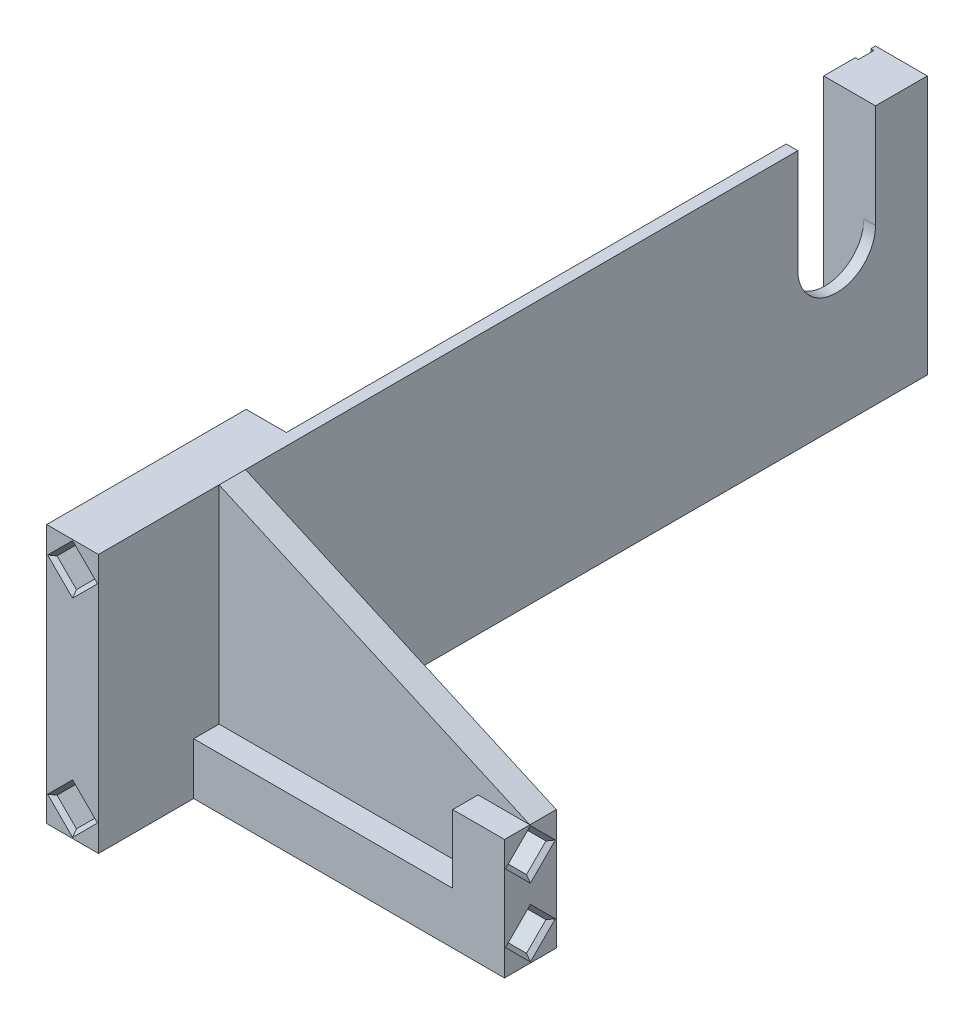
SolidWorks part; units mm, degrees
ref_plane "Front Plane" through (0, 0, 0) normal (0, 0, 1) x (1, 0, 0)
ref_plane "Top Plane" through (0, 0, 0) normal (0, 1, 0) x (1, 0, 0)
ref_plane "Right Plane" through (0, 0, 0) normal (1, 0, 0) x (0, 0, -1)
sketch "Sketch2" plane through (0, 0, 0) normal (0, 1, 0) x (1, 0, 0)
  line L0 (25.75, 56.5) -> (25.75, 62.5) construction
  line L1 (31.75, 62.5) -> (-31.75, 62.5) construction
  line L2 (31.75, 62.5) -> (31.75, -62.5) construction
  line L3 (31.75, -62.5) -> (-31.75, -62.5) construction
  line L4 (-31.75, 62.5) -> (-31.75, -62.5) construction
  line L5 (25.75, 56.5) -> (31.75, 56.5) construction
  line L6 (-25.75, -56.5) -> (-31.75, -56.5) construction
  line L7 (-25.75, -56.5) -> (-25.75, -62.5) construction
  point P4 (0, -56.5)
  point P5 (25.75, -56.5)
  point P6 (0, 56.5)
  point P8 (25.75, 56.5)
  point P12 (-25.75, -56.5)
  point P13 (0, -62.5)
  point P14 (-25.75, 56.5)
  point P17 (31.75, 0)
  dimension "D1" = 63.5
  dimension "D2" = 125
  dimension "D3" = 6
  dimension "D4" = 6
sketch "Sketch3" plane through (0, 0, 0) normal (0, 1, 0) x (1, 0, 0)
  line L0 (-31.75, 62.5) -> (-31.75, -62.5) construction
  line L1 (-29.21, 50.2117) -> (-37.6767, 50.2117)
  line L2 (-29.21, 50.2117) -> (-29.21, -61.23)
  line L3 (-29.21, -85.255) -> (-37.6767, -85.255)
  line L4 (-37.6767, 50.2117) -> (-37.6767, -85.255)
  line L6 (31.75, -62.5) -> (-31.75, -62.5) construction
  line L8 (-29.21, -61.23) -> (21.59, -61.23)
  line L10 (-29.21, -69.6967) -> (21.59, -69.6967)
  line L11 (21.59, -61.23) -> (21.59, -69.6967)
  line L13 (-29.21, -69.6967) -> (-29.21, -85.255)
  point P4 (-33.4433, 50.2117)
  dimension "D1" = 135.4667
  dimension "D2" = 8.4667
  dimension "D3" = 1.27
  dimension "D4" = 1.6933
  dimension "D5" = 50.8
  dimension "D6" = 15.5583
  dimension "D7" = 8.4667
extrude "Boss-Extrude2" add sketch "Sketch3" along normal blind 8.4667
sketch "Sketch12" plane through (0, 0, 0) normal (0, 1, 0) x (1, 0, 0)
  line L2 (-29.21, -61.23) -> (-29.21, 50.2117) construction
  line L5 (-25.75, -51.77) -> (-29.21, -51.77)
  line L6 (-25.75, -61.23) -> (-29.21, -61.23)
  line L7 (-29.21, -51.77) -> (-29.21, -61.23)
  line L8 (-25.75, -56.5) -> (-25.75, -62.5) construction
  line L9 (21.59, -61.23) -> (-29.21, -61.23) construction
  arc A1 (-25.75, -61.23) -> (-25.75, -51.77) centre (-25.75, -56.5) ccw
extrude "Boss-Extrude4" add sketch "Sketch12" along normal blind 3.175
sketch "Sketch14" plane through (0, 3.175, 0) normal (0, 1, 0) x (1, 0, 0)
  point P0 (-25.75, 56.5)
  point P1 (-25.75, -56.5)
hole_wizard "#24 (0.152) Diameter Hole1" positions "Sketch14" profile "Sketch15" hole size "#24" standard "ANSI Inch" end condition up to next
sketch "Sketch15" plane through (-25.75, 3.175, -56.5) normal (1, 0, 0) x (0, 0, 1)
  line L0 (0, 0) -> (0, 3.175)
  line L1 (0, 3.175) -> (1.9304, 3.175)
  line L2 (1.9304, 3.175) -> (1.9304, 0)
  line L5 (1.9304, 0) -> (0, 0)
  line L11 (0, -6.35) -> (0, 107.95) construction
  dimension "Thru Hole Dia." = 3.8608
  dimension "Thru Hole Depth" = 3.175
sketch "Sketch16" plane through (0, 8.4667, 0) normal (0, 1, 0) x (1, 0, 0)
  line L0 (-37.6767, -85.255) -> (-37.6767, -52.6472)
  line L1 (-29.21, -61.23) -> (-29.21, 50.2117) construction
  line L2 (-37.6767, 50.2117) -> (-29.21, 50.2117)
  line L5 (-37.6767, 41.745) -> (-31.115, 41.745)
  line L6 (-31.115, 41.745) -> (-31.115, -52.6472)
  line L7 (-31.115, -52.6472) -> (-37.6767, -52.6472)
  line L8 (-37.6767, 41.745) -> (-37.6767, 50.2117)
  line L9 (-29.21, -5.5092) -> (-31.115, -5.5092) construction
  line L11 (-37.6767, 50.2117) -> (-37.6767, -85.255) construction
  line L12 (-29.21, -85.255) -> (-37.6767, -85.255)
  line L13 (-29.21, -85.255) -> (-29.21, 50.2117)
  line L16 (-29.21, -61.23) -> (-29.21, 50.2117) construction
  dimension "D1" = 1.905
  dimension "D2" = 8.4667
extrude "Boss-Extrude5" add sketch "Sketch16" along normal blind 33.8667
sketch "Sketch19" plane through (0, 8.4667, 0) normal (0, 1, 0) x (1, 0, 0)
  line L0 (-29.21, -69.6967) -> (21.59, -69.6967) construction
  line L1 (21.59, -61.23) -> (13.1233, -61.23)
  line L2 (21.59, -61.23) -> (21.59, -69.6967)
  line L3 (21.59, -69.6967) -> (13.1233, -69.6967)
  line L4 (13.1233, -61.23) -> (13.1233, -69.6967)
extrude "Boss-Extrude7" add sketch "Sketch19" along normal blind 11.1417
sketch "Sketch18" plane through (0, 0, 61.23) normal (0, 0, -1) x (-1, 0, 0)
  line L0 (-21.59, 19.6083) -> (29.21, 42.3333)
  line L1 (-13.1233, 8.4667) -> (29.21, 8.4667) construction
  line L3 (29.21, 42.3333) -> (37.6767, 42.3333) construction
  line L4 (29.21, 42.3333) -> (29.21, 0) construction
  line L5 (29.21, 42.3333) -> (29.21, 8.4667)
  line L8 (-21.59, 19.6083) -> (-21.59, 0) construction
  line L9 (-21.59, 19.6083) -> (-13.1233, 19.6083)
  line L10 (-13.1233, 19.6083) -> (-13.1233, 8.4667)
  line L11 (-13.1233, 8.4667) -> (29.21, 8.4667)
extrude "Boss-Extrude6" add sketch "Sketch18" against normal blind 4.318
sketch "Sketch4" plane through (0, 0, 85.255) normal (0, 0, 1) x (1, 0, 0)
  line L0 (-36.6183, 4.2333) -> (-33.4433, 7.4083)
  line L1 (-36.6183, 4.2333) -> (-33.4433, 1.0583)
  line L2 (-33.4433, 7.4083) -> (-30.2683, 4.2333)
  line L3 (-33.4433, 1.0583) -> (-30.2683, 4.2333)
  line L4 (-36.6183, 4.2333) -> (-30.2683, 4.2333) construction
  line L5 (-33.4433, 7.4083) -> (-33.4433, 1.0583) construction
  line L6 (-37.6767, 8.4667) -> (-29.21, 8.4667) construction
  line L8 (-36.6183, 38.1) -> (-33.4433, 41.275)
  line L9 (-36.6183, 38.1) -> (-33.4433, 34.925)
  line L10 (-33.4433, 41.275) -> (-30.2683, 38.1)
  line L11 (-33.4433, 34.925) -> (-30.2683, 38.1)
  line L12 (-36.6183, 38.1) -> (-30.2683, 38.1) construction
  line L13 (-33.4433, 41.275) -> (-33.4433, 34.925) construction
  line L14 (-37.6767, 42.3333) -> (-29.21, 42.3333) construction
  line L15 (-37.6767, 0) -> (-29.21, 0) construction
  point P1 (-33.4433, 4.2333)
  point P3 (-33.4433, 8.4667)
  point P12 (-33.4433, 38.1)
  dimension "D1" = 6.35
  dimension "D2" = 4.2333
  dimension "D3" = 4.2333
extrude "RightPins" cut sketch "Sketch4" against normal blind 6.35
sketch "Sketch5" plane through (0, 0, -50.2117) normal (0, 0, -1) x (-1, 0, 0)
  line L0 (30.2683, 4.2333) -> (33.4433, 7.4083)
  line L1 (30.2683, 4.2333) -> (33.4433, 1.0583)
  line L2 (33.4433, 7.4083) -> (36.6183, 4.2333)
  line L3 (33.4433, 1.0583) -> (36.6183, 4.2333)
  line L4 (30.2683, 4.2333) -> (36.6183, 4.2333) construction
  line L5 (33.4433, 7.4083) -> (33.4433, 1.0583) construction
  line L6 (29.21, 8.4667) -> (37.6767, 8.4667) construction
  line L8 (29.21, 0) -> (37.6767, 0) construction
  line L9 (30.2683, 38.1) -> (33.4433, 41.275)
  line L10 (30.2683, 38.1) -> (33.4433, 34.925)
  line L11 (33.4433, 41.275) -> (36.6183, 38.1)
  line L12 (33.4433, 34.925) -> (36.6183, 38.1)
  line L13 (30.2683, 38.1) -> (36.6183, 38.1) construction
  line L14 (33.4433, 41.275) -> (33.4433, 34.925) construction
  line L16 (29.21, 42.3333) -> (37.6767, 42.3333) construction
  point P1 (33.4433, 4.2333)
  point P8 (33.4433, 8.4667)
  point P11 (33.4433, 38.1)
  dimension "D1" = 6.35
  dimension "D2" = 4.2333
  dimension "D3" = 4.2333
extrude "LeftPins" cut sketch "Sketch5" against normal blind 6.35
sketch "Sketch11" plane through (21.59, 0, 0) normal (1, 0, 0) x (0, 0, -1)
  line L0 (-68.6383, 4.2333) -> (-65.4633, 7.4083)
  line L1 (-68.6383, 4.2333) -> (-65.4633, 1.0583)
  line L2 (-65.4633, 7.4083) -> (-62.2883, 4.2333)
  line L3 (-65.4633, 1.0583) -> (-62.2883, 4.2333)
  line L4 (-68.6383, 4.2333) -> (-62.2883, 4.2333) construction
  line L5 (-65.4633, 7.4083) -> (-65.4633, 1.0583) construction
  line L6 (-69.6967, 8.4667) -> (-61.23, 8.4667) construction
  line L7 (-68.6383, 15.375) -> (-65.4633, 18.55)
  line L8 (-69.6967, 0) -> (-61.23, 0) construction
  line L9 (-68.6383, 15.375) -> (-65.4633, 12.2)
  line L10 (-65.4633, 18.55) -> (-62.2883, 15.375)
  line L11 (-65.4633, 12.2) -> (-62.2883, 15.375)
  line L12 (-68.6383, 15.375) -> (-62.2883, 15.375) construction
  line L13 (-65.4633, 18.55) -> (-65.4633, 12.2) construction
  line L14 (-69.6967, 19.6083) -> (-65.548, 19.6083) construction
  point P1 (-65.4633, 4.2333)
  point P3 (-65.4633, 8.4667)
  point P11 (-65.4633, 15.375)
  dimension "D1" = 6.35
  dimension "D2" = 4.2333
  dimension "D3" = 4.2333
extrude "FrontPins" cut sketch "Sketch11" against normal blind 6.35
chamfer "PinChamfer" distance 0.635 angle 45 48 edges at (-35.0308, 5.8208, -50.2117) (-31.8558, 5.8208, -50.2117) (-31.8558, 2.6458, -50.2117) (-35.0308, 2.6458, -50.2117) (-31.8558, 5.8208, -43.8617) (-35.0308, 5.8208, -43.8617) (-35.0308, 2.6458, -43.8617) (-31.8558, 2.6458, -43.8617) (-35.0308, 5.8208, 78.905) (-31.8558, 5.8208, 78.905) (-31.8558, 2.6458, 78.905) (-35.0308, 2.6458, 78.905) (-31.8558, 5.8208, 85.255) (-35.0308, 5.8208, 85.255) (-35.0308, 2.6458, 85.255) (-31.8558, 2.6458, 85.255) (15.24, 5.8208, 67.0508) (15.24, 5.8208, 63.8758) (15.24, 2.6458, 63.8758) (15.24, 2.6458, 67.0508) (21.59, 2.6458, 67.0508) (21.59, 2.6458, 63.8758) (21.59, 5.8208, 63.8758) (21.59, 5.8208, 67.0508) (-31.8558, 39.6875, -43.8617) (-35.0308, 39.6875, -43.8617) (-35.0308, 36.5125, -43.8617) (-31.8558, 36.5125, -43.8617) (-35.0308, 39.6875, 78.905) (-31.8558, 39.6875, 78.905) (-31.8558, 36.5125, 78.905) (-35.0308, 36.5125, 78.905) (-35.0308, 39.6875, -50.2117) (-35.0308, 36.5125, -50.2117) (-31.8558, 36.5125, -50.2117) (-31.8558, 39.6875, -50.2117) (-31.8558, 39.6875, 85.255) (-31.8558, 36.5125, 85.255) (-35.0308, 36.5125, 85.255) (-35.0308, 39.6875, 85.255) (15.24, 16.9625, 67.0508) (15.24, 16.9625, 63.8758) (15.24, 13.7875, 63.8758) (15.24, 13.7875, 67.0508) (21.59, 16.9625, 63.8758) (21.59, 13.7875, 63.8758) (21.59, 13.7875, 67.0508) (21.59, 16.9625, 67.0508)
sketch "Sketch20" plane through (-29.21, 0, 0) normal (1, 0, 0) x (0, 0, -1)
  line L0 (41.745, 42.3333) -> (41.745, 8.4667) construction
  line L1 (41.745, 25.4) -> (41.745, 42.3333)
  line L2 (-61.23, 42.3333) -> (50.2117, 42.3333) construction
  line L3 (41.745, 42.3333) -> (29.045, 42.3333)
  line L4 (29.045, 42.3333) -> (29.045, 25.4)
  line L6 (62.5, 0) -> (-62.5, 0) construction
  arc A0 (29.045, 25.4) -> (41.745, 25.4) centre (35.395, 25.4) ccw
  dimension "D1" = 6.35
  dimension "D2" = 25.4
extrude "Cut-Extrude1" cut sketch "Sketch20" against normal up to next
sketch "Sketch21" plane through (0, 42.3333, 0) normal (0, 1, 0) x (1, 0, 0)
  line L0 (-37.6767, 50.2117) -> (-37.6767, 41.745) construction
  line L1 (-37.6767, 49.4497) -> (-37.1687, 49.4497)
  line L2 (-37.6767, 49.4497) -> (-37.6767, 46.9097)
  line L3 (-37.6767, 46.9097) -> (-37.1687, 46.9097)
  line L4 (-37.1687, 49.4497) -> (-37.1687, 46.9097)
  line L5 (-29.21, 50.2117) -> (-37.6767, 50.2117) construction
  dimension "D1" = 0.762
  dimension "D2" = 2.54
  dimension "D3" = 0.508
extrude "Cut-Extrude2" cut sketch "Sketch21" against normal up to next
